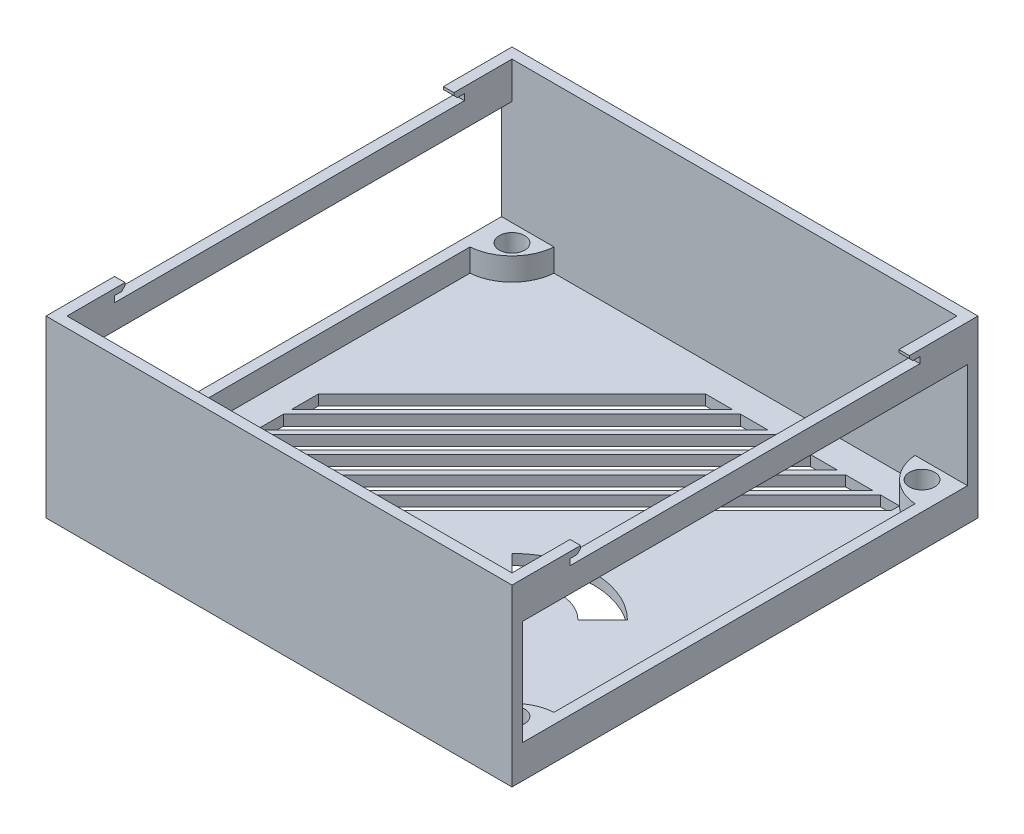
SolidWorks part; units mm, degrees
ref_plane "Front Plane" through (0, 0, 0) normal (0, 0, 1) x (1, 0, 0)
ref_plane "Top Plane" through (0, 0, 0) normal (0, 1, 0) x (1, 0, 0)
ref_plane "Right Plane" through (0, 0, 0) normal (1, 0, 0) x (0, 0, -1)
sketch "Sketch1" plane through (0, 0, 0) normal (0, 1, 0) x (1, 0, 0)
  line L0 (-66.6, -66.6) -> (-66.6, 66.6)
  line L1 (63.6, -63.6) -> (-63.6, -63.6)
  line L2 (63.6, -63.6) -> (63.6, 63.6)
  line L3 (63.6, 63.6) -> (-63.6, 63.6)
  line L4 (-63.6, -63.6) -> (-63.6, 63.6)
  line L5 (63.6, -63.6) -> (-63.6, 63.6) construction
  line L6 (63.6, 63.6) -> (-63.6, -63.6) construction
  line L7 (66.6, 66.6) -> (-66.6, 66.6)
  line L8 (66.6, -66.6) -> (66.6, 66.6)
  line L9 (66.6, -66.6) -> (-66.6, -66.6)
  point P0 (0, 0)
  dimension "D1" = 127.2
  dimension "D2" = 127.2
  dimension "D3" = 3
extrude "Boss-Extrude1" add sketch "Sketch1" along normal blind 50
sketch "Sketch2" plane through (0, 0, 0) normal (0, 1, 0) x (1, 0, 0)
  line L1 (63.6, 63.6) -> (-63.6, 63.6)
  line L2 (63.6, 63.6) -> (63.6, -63.6)
  line L3 (63.6, -63.6) -> (-63.6, -63.6)
  line L4 (-63.6, 63.6) -> (-63.6, -63.6)
  line L5 (63.6, 63.6) -> (-63.6, -63.6) construction
  line L6 (63.6, -63.6) -> (-63.6, 63.6) construction
  point P0 (0, 0)
extrude "Boss-Extrude2" add sketch "Sketch2" along normal blind 3
sketch "Sketch3" plane through (0, 3, 0) normal (0, 1, 0) x (1, 0, 0)
  line L0 (-63.6, 63.6) -> (-63.6, 58.6) construction
  line L1 (-63.6, 63.6) -> (-63.6, -63.6) construction
  line L2 (-63.6, 58.6) -> (63.6, 58.6) construction
  line L3 (63.6, -63.6) -> (63.6, 63.6) construction
  line L4 (-63.6, 63.6) -> (-58.6, 63.6) construction
  line L5 (63.6, 63.6) -> (-63.6, 63.6) construction
  line L6 (-58.6, 63.6) -> (-58.6, -63.6) construction
  line L7 (-63.6, -63.6) -> (63.6, -63.6) construction
  line L8 (-63.6, -63.6) -> (-63.6, -58.6) construction
  line L9 (-63.6, -58.6) -> (63.6, -58.6) construction
  line L10 (63.6, -63.6) -> (58.6, -63.6) construction
  line L11 (-63.6, -63.6) -> (63.6, -63.6) construction
  line L12 (58.6, -63.6) -> (58.6, 63.6) construction
  line L13 (-63.6, -63.6) -> (-63.6, -51.6) construction
  line L14 (-63.6, -63.6) -> (-51.9027, -63.6) construction
  line L15 (63.6, -63.6) -> (51.6, -63.6) construction
  line L16 (63.6, -63.6) -> (63.6, -51.6) construction
  line L17 (-51.6, 63.6) -> (-63.6, 63.6) construction
  line L18 (-63.6, 63.6) -> (-63.6, 51.6) construction
  line L19 (63.6, 63.6) -> (51.6, 63.6) construction
  line L20 (63.6, 63.6) -> (-63.6, 63.6) construction
  line L21 (63.6, 63.6) -> (63.6, 51.6105) construction
  line L22 (63.6, -63.6) -> (63.6, 63.6) construction
  line L23 (-51.6, 63.6) -> (-63.6, 63.6)
  line L24 (-63.6, 63.6) -> (-63.6, 51.6)
  line L25 (-63.6, -51.6) -> (-63.6, -63.6)
  line L26 (-63.6, -63.6) -> (-51.9027, -63.6)
  line L27 (51.6, 63.6) -> (63.6, 63.6)
  line L28 (63.6, 63.6) -> (63.6, 51.6105)
  line L29 (51.6, -63.6) -> (63.6, -63.6)
  line L30 (63.6, -63.6) -> (63.6, -51.6)
  circle A0 centre (-58.6, 58.6) radius 1.625
  circle A1 centre (58.6, 58.6) radius 1.625
  circle A2 centre (58.6, -58.6) radius 1.625
  circle A3 centre (-58.6, -58.6) radius 1.625
  circle A4 centre (-58.6, 58.6) radius 3.625
  circle A5 centre (58.6, 58.6) radius 3.625
  circle A6 centre (-58.6, -58.6) radius 3.625
  circle A7 centre (58.6, -58.6) radius 3.625
  arc A8 (-51.6, 63.6) -> (-63.6, 51.6) centre (-64.5642, 64.5642) cw
  arc A9 (-63.6, -51.6) -> (-51.9027, -63.6) centre (-64.8688, -64.5379) cw
  arc A10 (63.6, -51.6) -> (51.6, -63.6) centre (64.5642, -64.5642) ccw
  arc A11 (51.6, 63.6) -> (63.6, 51.6105) centre (64.5634, 64.5747) ccw
  line M1 (-63.6, 63.6) -> (-63.6, -63.6)
  line M2 (-63.6, -63.6) -> (63.6, -63.6)
  line M3 (63.6, -63.6) -> (63.6, 63.6)
  line M4 (63.6, 63.6) -> (-63.6, 63.6)
  dimension "D1" = 3.25
  dimension "D2" = 3.25
  dimension "D3" = 3.25
  dimension "D4" = 3.25
  dimension "D6" = 13
  dimension "D9" = 13
  dimension "D7" = 12
  dimension "D8" = 12
  dimension "D10" = 12
  dimension "D5" = 2
extrude "Boss-Extrude4" add sketch "Sketch3" along normal blind 7 and the other way blind 3 contours A8 A4 M4 M1 | A9 A6 M1 M2 | A11 A5 M4 M3 | A10 A7 M3 M2
sketch "Sketch4" plane through (66.6, 0, 0) normal (1, 0, 0) x (0, 0, -1)
  line L0 (-66.6, 0) -> (-66.6, 9.5) construction
  line L1 (-66.6, 50) -> (-66.6, 0) construction
  line L2 (-66.6, 9.5) -> (-63.6, 9.5) construction
  line L3 (66.6, 9.5) -> (63.6, 9.5) construction
  line L4 (66.6, 50) -> (66.6, 0) construction
  line L5 (63.6, 9.5) -> (63.6, 39.5) construction
  line L7 (63.6, 39.5) -> (-63.6, 39.5)
  line L8 (63.6, 39.5) -> (63.6, 9.5)
  line L9 (63.6, 9.5) -> (-63.6, 9.5)
  line L10 (-63.6, 39.5) -> (-63.6, 9.5)
extrude "Cut-Extrude2" cut sketch "Sketch4" against normal through all
sketch "Sketch5" plane through (66.6, 0, 0) normal (1, 0, 0) x (0, 0, -1)
  line L0 (-66.6, 50) -> (-50, 50) construction
  line L1 (0, 50) -> (0, 46.5) construction
  line L2 (0, 46.5) -> (-50, 46.5) construction
  line L3 (0, 46.5) -> (50, 46.5) construction
  line L4 (-50, 46.5) -> (-47, 46.5) construction
  line L5 (-50, 46.5) -> (50, 46.5)
  line L6 (-50, 46.5) -> (-50, 48.25)
  line L7 (-47, 50) -> (50, 50)
  line L8 (50, 46.5) -> (50, 48.25)
  line L9 (-47, 49.25) -> (-47, 50)
  line L10 (-48, 48.25) -> (-50, 48.25)
  line L11 (-47, 50) -> (66.6, 50) construction
  line L12 (-48, 48.25) -> (-47, 49.25)
  line L13 (-50, 46.5) -> (-47, 46.5) construction
  line L14 (50, 46.5) -> (47, 46.5) construction
  line L15 (47, 46.5) -> (47, 50) construction
  line L16 (48, 48.25) -> (50, 48.25)
  line L17 (47, 49.25) -> (47, 50)
  line L18 (48, 48.25) -> (47, 49.25)
  line L19 (-47, 50) -> (47, 50)
  point P11 (-47, 48.25)
  point P19 (47, 48.25)
  dimension "D1" = 1.75
  dimension "D2" = 1.75
extrude "Cut-Extrude3" cut sketch "Sketch5" against normal through all contours L16 L18 L17 L7 L9 L12 L10 L6 L5 L8
sketch "Sketch6" plane through (0, 3, 0) normal (0, 1, 0) x (1, 0, 0)
  line L0 (13.8451, 51.5267) -> (17.6902, 55.3718)
  line L1 (10, 55.3718) -> (17.6902, 55.3718)
  line L2 (0, 55.3718) -> (-55.3718, 0)
  line L3 (-55.3718, -50) -> (-55.3718, -55.3718)
  line L4 (55.3718, 55.3718) -> (55.3718, 53.0534)
  line L5 (51.8363, -51.8363) -> (4.6947, -4.6947)
  line L6 (28.2655, -28.2655) -> (51.8363, -4.6947)
  line L7 (10, 55.3718) -> (-45.3718, 0)
  line L8 (13.8451, 51.5267) -> (-41.5267, -3.8451)
  line L9 (3.8451, 51.5267) -> (-51.5267, -3.8451)
  line L10 (3.8451, 51.5267) -> (7.6902, 55.3718)
  line L11 (-51.5267, -3.8451) -> (-55.3718, -7.6902)
  line L12 (-55.3718, -7.6902) -> (-55.3718, 0)
  line L13 (0, 55.3718) -> (7.6902, 55.3718)
  line L14 (-41.5267, -3.8451) -> (-45.3718, -7.6902)
  line L15 (-45.3718, 0) -> (-55.3718, -10)
  line L16 (23.8451, 51.5267) -> (27.6902, 55.3718)
  line L17 (20, 55.3718) -> (27.6902, 55.3718)
  line L18 (20, 55.3718) -> (-35.3718, 0)
  line L19 (23.8451, 51.5267) -> (-31.5267, -3.8451)
  line L20 (-31.5267, -3.8451) -> (-35.3718, -7.6902)
  line L21 (-45.3718, -7.6902) -> (-55.3718, -17.6902)
  line L22 (33.8451, 51.5267) -> (37.6902, 55.3718)
  line L23 (30, 55.3718) -> (37.6902, 55.3718)
  line L24 (30, 55.3718) -> (-25.3718, 0)
  line L25 (33.8451, 51.5267) -> (-21.5267, -3.8451)
  line L26 (-21.5267, -3.8451) -> (-25.3718, -7.6902)
  line L27 (-55.3718, -17.6902) -> (-55.3718, -10)
  line L28 (43.8451, 51.5267) -> (47.6902, 55.3718)
  line L29 (40, 55.3718) -> (47.6902, 55.3718)
  line L30 (40, 55.3718) -> (-15.3718, 0)
  line L31 (43.8451, 51.5267) -> (-11.5267, -3.8451)
  line L32 (-11.5267, -3.8451) -> (-15.3718, -7.6902)
  line L33 (-35.3718, 0) -> (-55.3718, -20)
  line L34 (53.8451, 51.5267) -> (55.3718, 53.0534)
  line L35 (50, 55.3718) -> (55.3718, 55.3718)
  line L36 (50, 55.3718) -> (-5.3718, 0)
  line L37 (53.8451, 51.5267) -> (-1.5267, -3.8451)
  line L38 (-1.5267, -3.8451) -> (-5.3718, -7.6902)
  line L39 (-35.3718, -7.6902) -> (-55.3718, -27.6902)
  line L40 (-45.3718, -7.6902) -> (-45.3718, 0) [skipped]
  line L41 (-35.3718, -7.6902) -> (-35.3718, 0) [skipped]
  line L42 (-25.3718, -7.6902) -> (-25.3718, -2.0569) [skipped]
  line L43 (-15.3718, -7.6902) -> (-15.3718, -5.9836) [skipped]
  line L44 (-5.3718, -7.6902) -> (-5.3718, 0) [skipped]
  line L45 (-55.3718, -27.6902) -> (-55.3718, -20)
  line L46 (-25.3718, 0) -> (-55.3718, -30)
  line L47 (-25.3718, -7.6902) -> (-55.3718, -37.6902)
  line L48 (-55.3718, -37.6902) -> (-55.3718, -30)
  line L49 (-15.3718, 0) -> (-55.3718, -40)
  line L50 (-15.3718, -7.6902) -> (-55.3718, -47.6902)
  line L51 (-55.3718, -47.6902) -> (-55.3718, -40)
  line L52 (-5.3718, 0) -> (-55.3718, -50)
  line L53 (-5.3718, -7.6902) -> (-53.0534, -55.3718)
  line L54 (-53.0534, -55.3718) -> (-55.3718, -55.3718)
  line L55 (28.2655, -28.2655) -> (4.6947, -51.8363)
  circle A0 centre (28.2655, -28.2655) radius 13.3341 construction
  circle A1 centre (28.2655, -28.2655) radius 18.3341 construction
  circle A2 centre (28.2655, -28.2655) radius 23.3341 construction
  arc A3 (18.8369, -37.6941) -> (18.8369, -18.8369) centre (28.2655, -28.2655) ccw
  arc A4 (15.3013, -15.3013) -> (41.2297, -15.3013) centre (28.2655, -28.2655) ccw
  arc A5 (44.7652, -11.7658) -> (44.7652, -44.7652) centre (28.2655, -28.2655) ccw
  arc A6 (48.3007, -48.3007) -> (8.2303, -8.2303) centre (28.2655, -28.2655) ccw
  arc A7 (4.6947, -4.6947) -> (51.8363, -4.6947) centre (28.2655, -28.2655) ccw
  circle A8 centre (28.2655, -28.2655) radius 28.3341 construction
  circle A9 centre (28.2655, -28.2655) radius 33.3341 construction
  dimension "D2" = 5
  dimension "D3" = 5
  dimension "D4" = 5
  dimension "D5" = 5
  dimension "D1" = 6
extrude "Cut-Extrude6" cut sketch "Sketch6" against normal through all contours L54 L53 L38 L37 L34 L4 L35 L36 L52 L3 | L48 L47 L26 L25 L22 L23 L24 L46 | L45 L39 L20 L19 L16 L17 L18 L33 | L27 L21 L14 L8 L0 L1 L7 L15 | L13 L2 L12 L11 L9 L10 | L55 A3 L5 | L6 A5 L5 A3 | L49 L51 L50 L32 L31 L28 L29 L30
